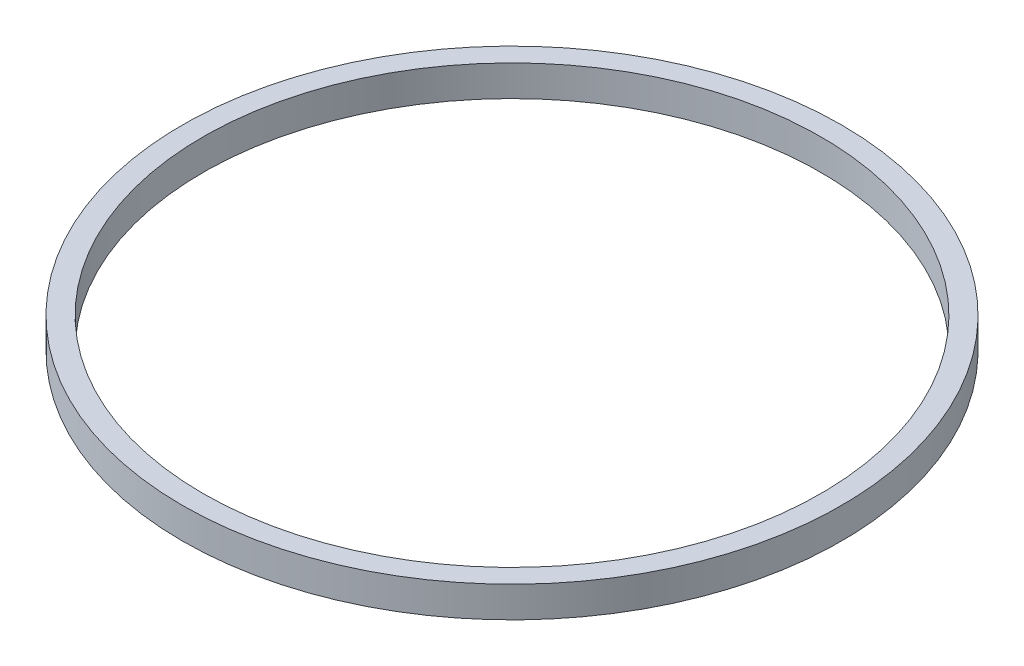
SolidWorks part; units mm, degrees
ref_plane "Front Plane" through (0, 0, 0) normal (0, 0, 1) x (1, 0, 0)
ref_plane "Top Plane" through (0, 0, 0) normal (0, 1, 0) x (1, 0, 0)
ref_plane "Right Plane" through (0, 0, 0) normal (1, 0, 0) x (0, 0, -1)
sketch "Sketch2" plane through (0, 0, 0) normal (0, 1, 0) x (1, 0, 0)
  circle A0 centre (0, 0) radius 32
  circle A1 centre (0, 0) radius 30
extrude "Boss-Extrude1" add sketch "Sketch2" along normal blind 3
